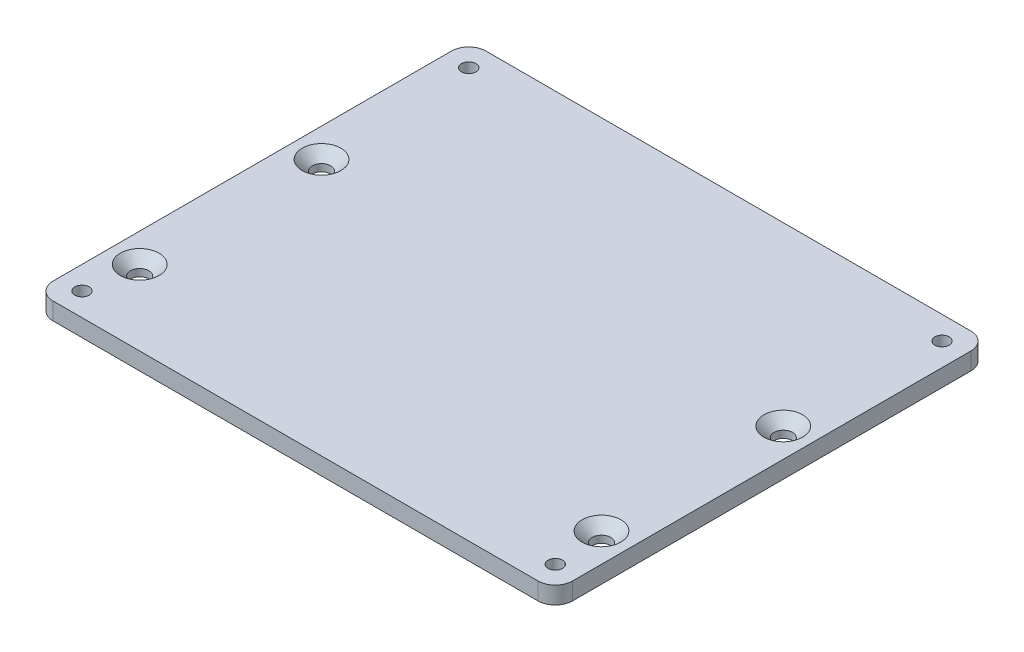
SolidWorks part; units mm, degrees
material "6061-T6 (SS)"
ref_plane "Front Plane" through (0, 0, 0) normal (0, 0, 1) x (1, 0, 0)
ref_plane "Top Plane" through (0, 0, 0) normal (0, 1, 0) x (1, 0, 0)
ref_plane "Right Plane" through (0, 0, 0) normal (1, 0, 0) x (0, 0, -1)
sketch "Sketch1" plane through (0, 0, 0) normal (0, 1, 0) x (1, 0, 0)
  line L1 (45, -37.5) -> (-45, -37.5)
  line L2 (45, -37.5) -> (45, 37.5)
  line L3 (45, 37.5) -> (-45, 37.5)
  line L4 (-45, -37.5) -> (-45, 37.5)
  line L5 (45, -37.5) -> (-45, 37.5) construction
  line L6 (45, 37.5) -> (-45, -37.5) construction
  point P0 (0, 0)
  dimension "D1" = 90
  dimension "D2" = 75
extrude "Boss-Extrude1" add sketch "Sketch1" along normal blind 3
hole_wizard "Tap Drill for M3x0.5 Tap1" positions "Sketch2" profile "Sketch4" hole size "M3x0.5" standard "ANSI Metric" end condition through all
sketch "Sketch2" plane through (0, 3, 0) normal (0, 1, 0) x (1, 0, 0)
  line L12 (-41, 33.5) -> (-41, -33.5)
  line L13 (-41, -33.5) -> (41, -33.5)
  line L14 (41, -33.5) -> (41, 33.5)
  line L15 (41, 33.5) -> (-41, 33.5)
  line L16 (-41, 33.5) -> (-41, -33.5)
  line L17 (-41, -33.5) -> (41, -33.5)
  line L18 (41, -33.5) -> (41, 33.5)
  line L19 (41, 33.5) -> (-41, 33.5)
  point P25 (-41, 33.5)
  point P26 (-41, -33.5)
  point P27 (41, -33.5)
  point P28 (41, 33.5)
  dimension "D1" = 4
sketch "Sketch4" plane through (-41, 3, -33.5) normal (1, 0, 0) x (0, 0, 1)
  line L0 (0, 0) -> (0, 3)
  line L1 (0, 3) -> (1.25, 3)
  line L2 (1.25, 3) -> (1.25, 0)
  line L5 (1.25, 0) -> (0, 0)
  line L11 (0, -6.35) -> (0, 107.95) construction
  dimension "Thru Hole Dia." = 2.5
  dimension "Thru Hole Depth" = 3
fillet "Fillet1" radius 3 4 edges at (45, 1.5, -37.5) (45, 1.5, 37.5) (-45, 1.5, 37.5) (-45, 1.5, -37.5)
sketch "Sketch5" plane through (0, 3, 0) normal (0, 1, 0) x (1, 0, 0)
  line L0 (-45, 34.5) -> (-45, -34.5) construction
  line L1 (40, -24.5) -> (-40, -24.5)
  line L2 (40, -24.5) -> (40, 7)
  line L3 (40, 7) -> (-40, 7)
  line L4 (-40, -24.5) -> (-40, 7)
  line L5 (40, -24.5) -> (-40, 7) construction
  line L6 (40, 7) -> (-40, -24.5) construction
  point P0 (0, -8.75)
  point P8 (-0.4497, 7.8951)
  point P9 (0, 8.6347)
  point P10 (0, -12.6594)
  dimension "D1" = 31.5
  dimension "D2" = 5
  dimension "D3" = 7
hole_wizard "CSK for M3 SFHCS1" positions "Sketch6" profile "Sketch7" countersink size "M3" standard "ANSI Metric" end condition through all
sketch "Sketch6" plane through (0, 3, 0) normal (0, 1, 0) x (1, 0, 0)
  point P0 (-40, 7)
  point P3 (-40, -24.5)
  point P6 (40, -24.5)
  point P9 (40, 7)
sketch "Sketch7" plane through (-40, 3, -7) normal (1, 0, 0) x (0, 0, 1)
  line L0 (0, 0) -> (0, 3)
  line L1 (0, 3) -> (1.6, 3)
  line L2 (1.6, 3) -> (1.6, 1.76)
  line L3 (1.6, 1.76) -> (3.36, 0)
  line L5 (3.36, 0) -> (0, 0)
  line L6 (-1.6, 1.76) -> (-3.36, 0) construction
  line L11 (0, -6.35) -> (0, 107.95) construction
  dimension "Thru Hole Dia." = 3.2
  dimension "Thru Hole Depth" = 3
  dimension "Near C'Sink Dia." = 6.72
  dimension "Near C'Sink Angle" = 90
